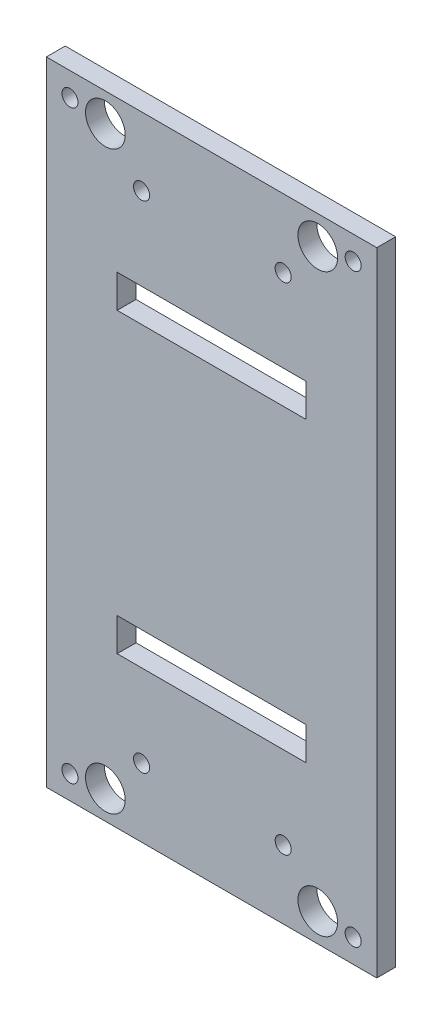
SolidWorks part; units mm, degrees
ref_plane "前视基准面" through (0, 0, 0) normal (0, 0, 1) x (1, 0, 0)
ref_plane "上视基准面" through (0, 0, 0) normal (0, 1, 0) x (1, 0, 0)
ref_plane "右视基准面" through (0, 0, 0) normal (1, 0, 0) x (0, 0, -1)
other "Configuration Table"
sketch "草图1" plane through (0, 0, 0) normal (0, 0, 1) x (1, 0, 0)
  line L1 (-35, -67) -> (35, -67)
  line L2 (-35, -67) -> (-35, 67)
  line L3 (-35, 67) -> (35, 67)
  line L4 (35, -67) -> (35, 67)
extrude "Controller_removable_central_tray" add sketch "草图1" along normal blind 4 from offset 57
sketch "草图2" plane through (0, 0, 0) normal (0, 0, 1) x (1, 0, 0)
  line L1 (-20, -35) -> (20, -35)
  line L2 (-20, -35) -> (-20, -28)
  line L3 (-20, -28) -> (20, -28)
  line L4 (20, -35) -> (20, -28)
  line L6 (-20, 28) -> (20, 28)
  line L7 (-20, 28) -> (-20, 35)
  line L8 (-20, 35) -> (20, 35)
  line L9 (20, 28) -> (20, 35)
  circle A0 centre (-30, -62) radius 1.7
  circle A1 centre (-30, 62) radius 1.7
  circle A2 centre (30, -62) radius 1.7
  circle A3 centre (30, 62) radius 1.7
  circle A4 centre (15.1723, -52.5) radius 1.7
  circle A5 centre (15.1723, 52.5) radius 1.7
  circle A6 centre (-14.8277, -52.5) radius 1.7
  circle A7 centre (-14.8277, 52.5) radius 1.7
extrude "Controller_flange_and_service_slots" cut sketch "草图2" against normal blind 6 from offset 62
sketch "草图3" plane through (0, 0, 0) normal (0, 0, 1) x (1, 0, 0)
  circle A0 centre (-22.5, -61) radius 4.2
  circle A1 centre (-22.5, 61) radius 4.2
  circle A2 centre (22.5, -61) radius 4.2
  circle A3 centre (22.5, 61) radius 4.2
extrude "Driver_post_and_fastener_clearance" cut sketch "草图3" against normal blind 6 from offset 62
